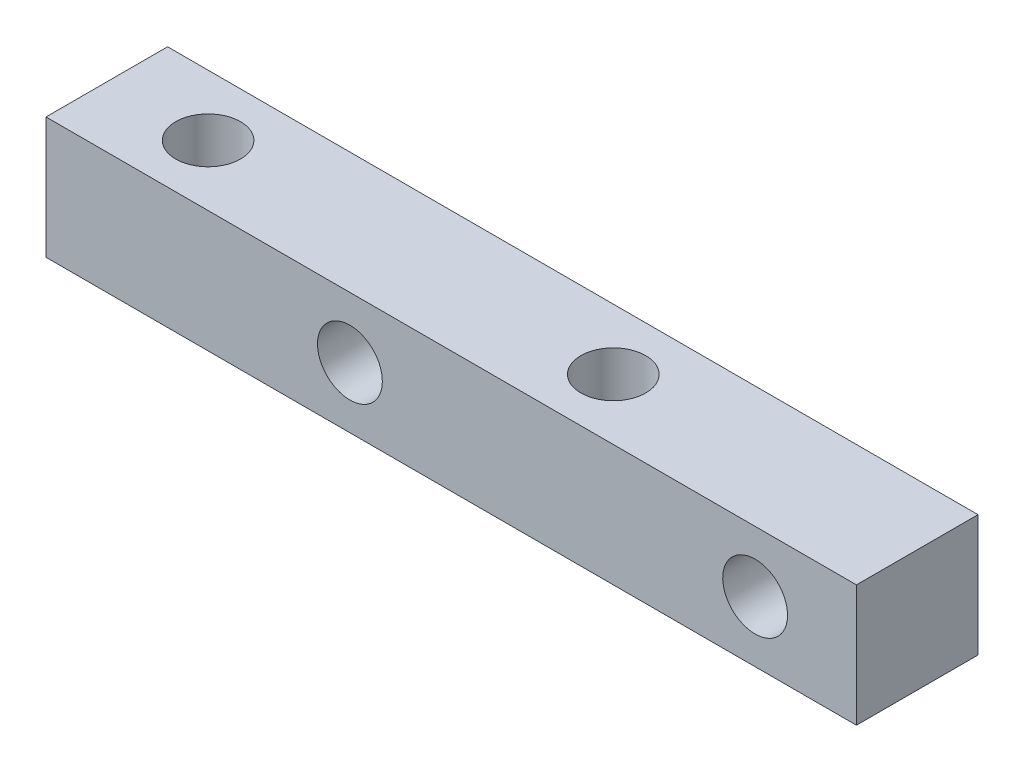
SolidWorks part; units mm, degrees
ref_plane "前视基准面" through (0, 0, 0) normal (0, 0, 1) x (1, 0, 0)
ref_plane "上视基准面" through (0, 0, 0) normal (0, 1, 0) x (1, 0, 0)
ref_plane "右视基准面" through (0, 0, 0) normal (1, 0, 0) x (0, 0, -1)
other "Configuration Table"
sketch "草图1" plane through (0, 0, 0) normal (1, 0, 0) x (0, 0, -1)
  line L1 (-3, 3) -> (3, 3)
  line L2 (-3, 3) -> (-3, -3)
  line L3 (-3, -3) -> (3, -3)
  line L4 (3, 3) -> (3, -3)
  line L5 (-3, 3) -> (3, -3) construction
  line L6 (-3, -3) -> (3, 3) construction
  point P0 (0, 0)
  dimension "D1" = 6
  dimension "D2" = 6
extrude "凸台-拉伸1" add sketch "草图1" along normal blind 40
sketch "草图2" plane through (0, 0, -3) normal (0, 0, -1) x (-1, 0, 0)
  line L0 (-40, 0) -> (0, 0) construction
  line L1 (-40, -3) -> (-40, 3) construction
  circle A0 centre (-35, 0) radius 1.6
  circle A1 centre (-15, 0) radius 1.6
  point P9 (0, 0)
  point P11 (-26.9083, 0)
  dimension "D1" = 3.2
  dimension "D2" = 5
  dimension "D3" = 20
extrude "切除-拉伸1" cut sketch "草图2" against normal through all
sketch "草图3" plane through (0, 3, 0) normal (0, 1, 0) x (1, 0, 0)
  line L0 (0, 0) -> (40, 0) construction
  line L1 (40, 3) -> (40, -3) construction
  line L2 (0, 3) -> (0, -3) construction
  circle A0 centre (5, 0) radius 1.6
  circle A1 centre (25, 0) radius 1.6
  dimension "D1" = 3.2
  dimension "D2" = 5
  dimension "D3" = 20
extrude "切除-拉伸2" cut sketch "草图3" against normal through all
